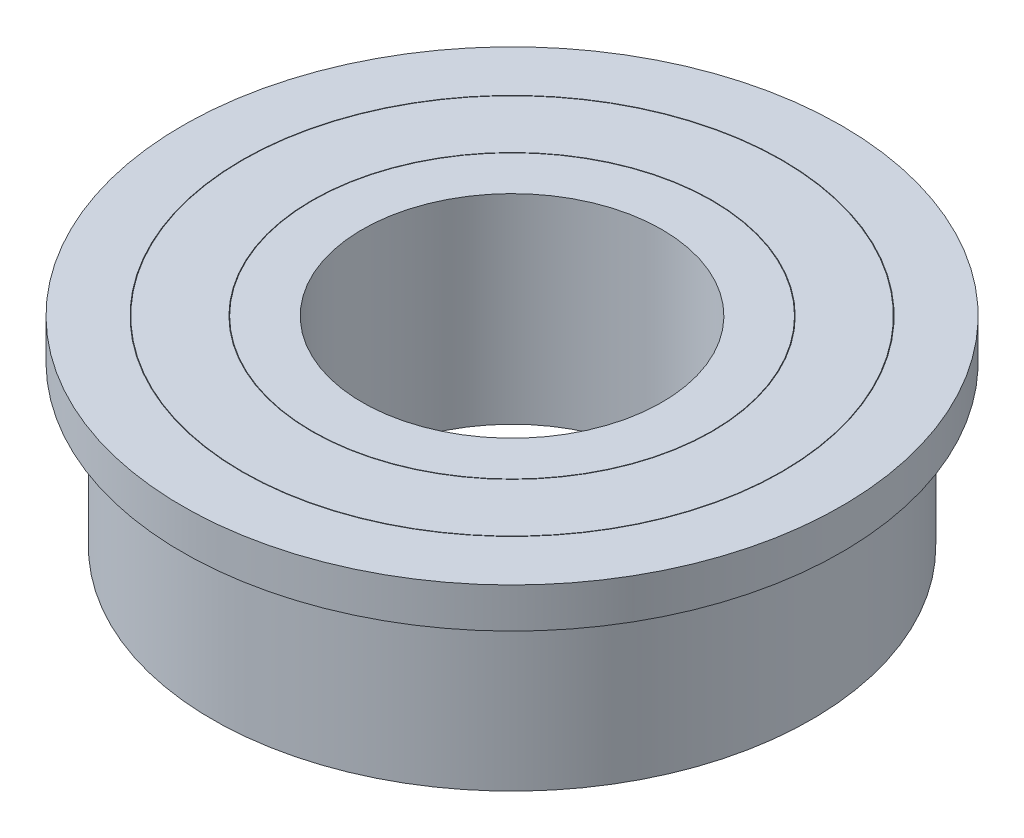
SolidWorks part; units mm, degrees
ref_plane "前视基准面" through (0, 0, 0) normal (0, 0, 1) x (1, 0, 0)
ref_plane "上视基准面" through (0, 0, 0) normal (0, 1, 0) x (1, 0, 0)
ref_plane "右视基准面" through (0, 0, 0) normal (1, 0, 0) x (0, 0, -1)
other "Configuration Table"
sketch "草图1" plane through (0, 0, 0) normal (1, 0, 0) x (0, 0, -1)
  line L0 (0, 0) -> (0, 15.6583) construction
  line L1 (-3, 0) -> (-4, 0)
  line L2 (-6, 0) -> (-6, 3.2)
  line L3 (-6, 3.2) -> (-6.6, 3.2)
  line L4 (-6.6, 3.2) -> (-6.6, 4)
  line L5 (-6.6, 4) -> (-5.41, 4)
  line L6 (-3, 4) -> (-3, 0)
  line L7 (-4.01, 0) -> (-4.01, 4)
  line L9 (-4, 4) -> (-4, 0)
  line L10 (-4.01, 0) -> (-5.4, 0)
  line L11 (-6, 3.2) -> (-3, 3.2) construction
  line L12 (-4.5, 3.2) -> (-4.5, 0) construction
  line L13 (-5.41, 0) -> (-6, 0)
  line L15 (-5.41, 0) -> (-5.41, 4)
  line L17 (-5.4, 0) -> (-5.4, 4)
  line L18 (-5.4, 4) -> (-4.01, 4)
  line L19 (-4, 4) -> (-3, 4)
  point P20 (-4.01, 4.2619)
  dimension "D1" = 3
  dimension "D2" = 6
  dimension "D3" = 6.6
  dimension "D4" = 0.8
  dimension "D5" = 4
  dimension "D6" = 0.01
  dimension "D7" = 0.01
  dimension "D8" = 4
  dimension "D10" = 0.6
revolve "旋转1" add sketch "草图1" angle 360 about L0
